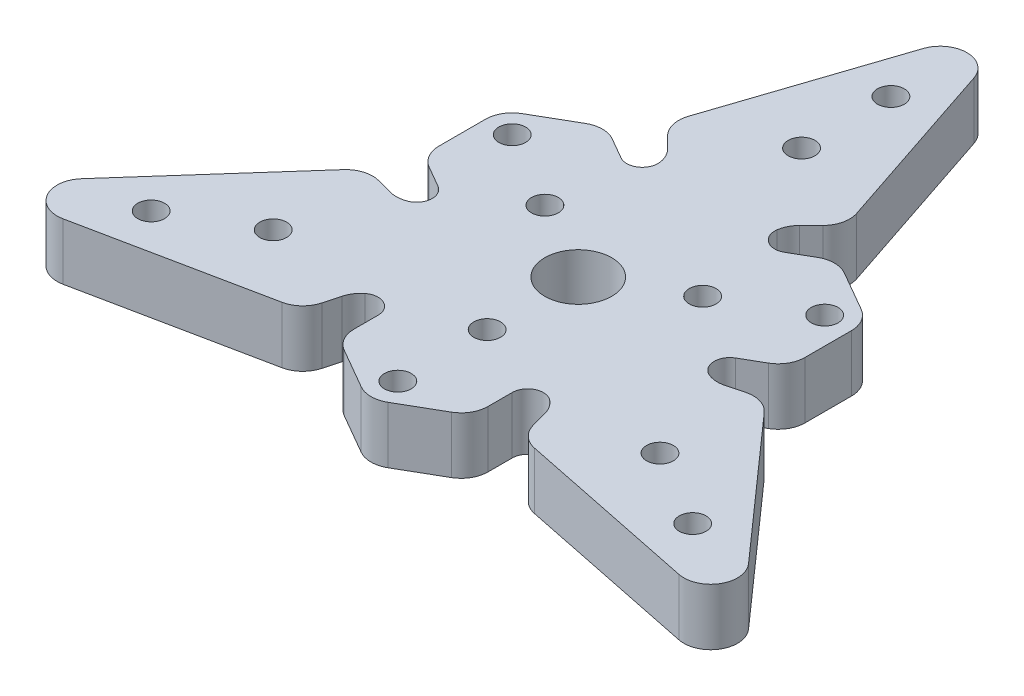
SolidWorks part; units mm, degrees
ref_plane "Front Plane" through (0, 0, 0) normal (0, 0, 1) x (1, 0, 0)
ref_plane "Top Plane" through (0, 0, 0) normal (0, 1, 0) x (1, 0, 0)
ref_plane "Right Plane" through (0, 0, 0) normal (1, 0, 0) x (0, 0, -1)
sketch "Sketch1" plane through (0, 0, 0) normal (0, 1, 0) x (1, 0, 0)
  line L51 (5.6921, 82.9237) -> (18.8274, 43.5179)
  line L52 (-5.6921, 82.9237) -> (-18.8274, 43.5179)
  line L53 (-17.3779, 37.3779) -> (-14.7962, 34.7962)
  line L54 (17.3779, 37.3779) -> (14.7962, 34.7962)
  line L55 (23.6813, -33.7387) -> (22.7363, -30.212)
  line L56 (68.968, -46.3914) -> (28.2739, -38.0639)
  line L57 (74.6601, -36.5323) -> (47.1013, -5.454)
  line L58 (41.0592, -3.6392) -> (37.5325, -4.5842)
  line L59 (-41.0592, -3.6392) -> (-37.5325, -4.5842)
  line L60 (-74.6601, -36.5323) -> (-47.1013, -5.454)
  line L61 (-68.968, -46.3914) -> (-28.2739, -38.0639)
  line L62 (-23.6813, -33.7387) -> (-22.7363, -30.212)
  line L63 (-40.9808, 20.1962) -> (-40.9808, 9.8038)
  line L64 (3, -45.5885) -> (12, -40.3923)
  line L65 (15, -35.1962) -> (15, -29.8108)
  line L68 (-15, -29.8108) -> (-15, -35.1962)
  line L69 (-12, -40.3923) -> (-3, -45.5885)
  line L70 (-37.9808, 4.6077) -> (-33.3169, 1.915)
  line L73 (-18.3169, 27.8958) -> (-22.9808, 30.5885)
  line L74 (-28.9808, 30.5885) -> (-37.9808, 25.3923)
  line L75 (37.9808, 25.3923) -> (28.9808, 30.5885)
  line L76 (22.9808, 30.5885) -> (18.3169, 27.8958)
  line L79 (33.3169, 1.915) -> (37.9808, 4.6077)
  line L80 (40.9808, 9.8038) -> (40.9808, 20.1962)
  line L83 (-7.5, -17.0096) -> (-15, -21.3397) [skipped]
  line L84 (7.5, -17.0096) -> (0, -12.6795) [skipped]
  circle A51 centre (0, 0) radius 7.5
  circle A76 centre (0, 70) radius 3
  circle A77 centre (0, 50) radius 3
  arc A78 (-5.6921, 82.9237) -> (5.6921, 82.9237) centre (0, 81.0263) cw
  arc A79 (-18.8274, 43.5179) -> (-17.3779, 37.3779) centre (-13.1353, 41.6205) ccw
  arc A80 (17.3779, 37.3779) -> (18.8274, 43.5179) centre (13.1353, 41.6205) ccw
  arc A81 (23.6813, -33.7387) -> (28.2739, -38.0639) centre (29.4768, -32.1857) ccw
  arc A82 (74.6601, -36.5323) -> (68.968, -46.3914) centre (70.1709, -40.5132) cw
  arc A83 (47.1013, -5.454) -> (41.0592, -3.6392) centre (42.6121, -9.4348) ccw
  circle A84 centre (60.6218, -35) radius 3
  circle A85 centre (43.3013, -25) radius 3
  arc A86 (-41.0592, -3.6392) -> (-47.1013, -5.454) centre (-42.6121, -9.4348) ccw
  arc A87 (-68.968, -46.3914) -> (-74.6601, -36.5323) centre (-70.1709, -40.5132) cw
  arc A88 (-28.2739, -38.0639) -> (-23.6813, -33.7387) centre (-29.4768, -32.1857) ccw
  circle A89 centre (-60.6218, -35) radius 3
  circle A90 centre (-43.3013, -25) radius 3
  arc A93 (22.7363, -30.212) -> (20.683, -27.075) centre (16.9407, -31.7649) ccw
  arc A94 (-37.5325, -4.5842) -> (-33.7891, -4.3745) centre (-35.9796, 1.2113) ccw
  arc A95 (-20.683, -27.075) -> (-22.7363, -30.212) centre (-16.9407, -31.7649) ccw
  arc A96 (13.1061, 31.4494) -> (14.7962, 34.7962) centre (19.0389, 30.5536) cw
  arc A97 (-13.1061, 31.4494) -> (-14.7962, 34.7962) centre (-19.0389, 30.5536) ccw
  arc A98 (33.7891, -4.3745) -> (37.5325, -4.5842) centre (35.9796, 1.2113) ccw
  arc A99 (-15, -30) -> (15, -30) centre (0, -30) ccw construction
  arc A100 (12, -40.3923) -> (15, -35.1962) centre (9, -35.1962) ccw
  arc A101 (3, -45.5885) -> (-3, -45.5885) centre (0, -40.3923) cw
  arc A102 (-15, -35.1962) -> (-12, -40.3923) centre (-9, -35.1962) ccw
  circle A103 centre (0, -40.3923) radius 3
  circle A104 centre (0, -20.3923) radius 3
  arc A105 (-40.9808, 20.1962) -> (-37.9808, 25.3923) centre (-34.9808, 20.1962) cw
  arc A106 (-40.9808, 9.8038) -> (-37.9808, 4.6077) centre (-34.9808, 9.8038) ccw
  arc A107 (-22.9808, 30.5885) -> (-28.9808, 30.5885) centre (-25.9808, 25.3923) ccw
  circle A108 centre (-34.9808, 20.1962) radius 3
  circle A109 centre (-17.6603, 10.1962) radius 3
  arc A110 (37.9808, 25.3923) -> (40.9808, 20.1962) centre (34.9808, 20.1962) cw
  arc A111 (28.9808, 30.5885) -> (22.9808, 30.5885) centre (25.9808, 25.3923) ccw
  arc A112 (37.9808, 4.6077) -> (40.9808, 9.8038) centre (34.9808, 9.8038) ccw
  circle A113 centre (34.9808, 20.1962) radius 3
  circle A114 centre (17.6603, 10.1962) radius 3
  arc A115 (18.3169, 27.8958) -> (13.1061, 31.4494) centre (16.5669, 30.9269) cw
  arc A116 (-18.3169, 27.8958) -> (-13.1061, 31.4494) centre (-16.5669, 30.9269) ccw
  arc A117 (-15, -29.8108) -> (-20.683, -27.075) centre (-18.5, -29.8108) ccw
  arc A118 (15, -29.8108) -> (20.683, -27.075) centre (18.5, -29.8108) cw
  arc A119 (-33.3169, 1.915) -> (-33.7891, -4.3745) centre (-35.0669, -1.1161) cw
  arc A120 (33.3169, 1.915) -> (33.7891, -4.3745) centre (35.0669, -1.1161) ccw
  point P2 (0, 20)
  point P4 (20, 40)
  point P18 (0, 0)
  point P19 (0, 0)
  point P22 (20, 40)
  point P24 (0, 0)
  point P27 (0, 0)
  point P33 (0, 0)
  point P35 (0, 0)
  point P43 (0, 0)
  point P47 (0, 0)
  point P53 (0, 0)
  point P56 (0.001, 0)
  point P59 (0, 0)
  point P62 (0, 0)
  point P67 (0, 0)
  point P90 (0, 0)
  point P128 (0, 0)
  dimension "D1" = 3
  dimension "D3" = 6
  dimension "D5" = 6
  dimension "D2" = 50
  dimension "D6" = 6
  dimension "D7" = 6
  dimension "D4" = 6
  dimension "D8" = 3
  dimension "D11" = 3
  dimension "D12" = 3.5
  dimension "D9" = 6
  dimension "D10" = 20
extrude "Boss-Extrude1" add sketch "Sketch1" along normal blind 12.7
sketch "Croquis1" plane through (0, 0, 0) normal (0, -1, 0) x (1, 0, 0)
  circle A0 centre (-60.6218, 35) radius 5.5
  circle A1 centre (-43.3013, 25) radius 5.5
  circle A2 centre (43.3013, 25) radius 5.5
  circle A3 centre (60.6218, 35) radius 5.5
  circle A4 centre (0, -50) radius 5.5
  circle A5 centre (0, -70) radius 5.5
extrude "Cortar-Extruir1" cut sketch "Croquis1" against normal blind 6
